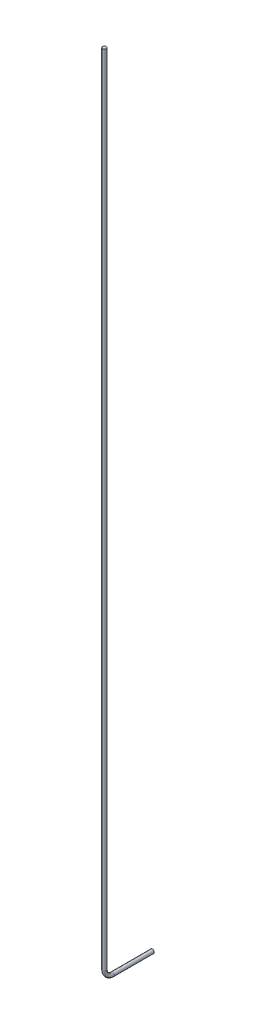
SolidWorks part; units mm, degrees
ref_plane "正面" through (0, 0, 0) normal (0, 0, 1) x (1, 0, 0)
ref_plane "平面" through (0, 0, 0) normal (0, 1, 0) x (1, 0, 0)
ref_plane "右側面" through (0, 0, 0) normal (1, 0, 0) x (0, 0, -1)
sketch "ｽｹｯﾁ1" plane through (0, 0, 0) normal (0, 0, 1) x (1, 0, 0)
  circle A0 centre (0, 0) radius 1.2
  dimension "D1" = 2.4
extrude "ﾎﾞｽ - 押し出し1" add sketch "ｽｹｯﾁ1" along normal blind 20
sketch "ｽｹｯﾁ2" plane through (0, 0, 20) normal (0, 0, 1) x (1, 0, 0)
  circle A1 centre (0, 0) radius 1.2
  circle A2 centre (0, 0) radius 1.2
  dimension "D1" = 0
sketch "ｽｹｯﾁ3" plane through (0, 0, 0) normal (1, 0, 0) x (0, 0, -1)
  line L0 (-20, 0) -> (-25, 0)
  line L1 (-20, 1.2) -> (-20, -1.2) construction
  line L2 (-30, 5) -> (-30, 505)
  line L3 (-20, 1.2) -> (-20, -1.2) construction
  arc A0 (-25, 0) -> (-30, 5) centre (-25, 5) cw
  point P8 (-30, 0)
  dimension "D2" = 5
  dimension "D1" = 10
  dimension "D3" = 500
sweep "ｽｲｰﾌﾟ1" add profiles "ｽｹｯﾁ2" path "ｽｹｯﾁ3"
